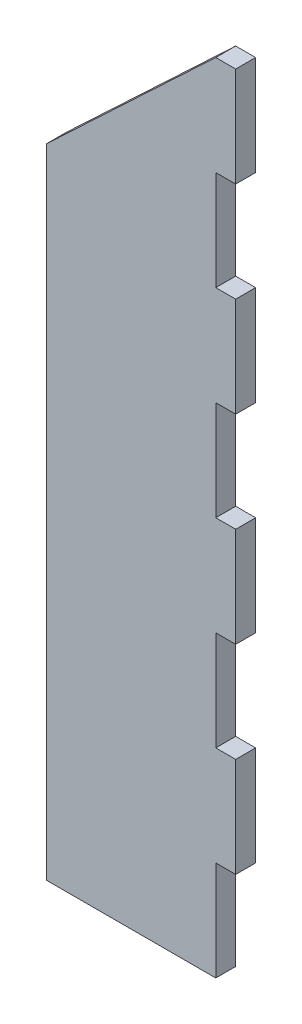
SolidWorks part; units mm, degrees
ref_plane "Front Plane" through (0, 0, 0) normal (0, 0, 1) x (1, 0, 0)
ref_plane "Top Plane" through (0, 0, 0) normal (0, 1, 0) x (1, 0, 0)
ref_plane "Right Plane" through (0, 0, 0) normal (1, 0, 0) x (0, 0, -1)
sketch "Sketch1" plane through (0, 0, 0) normal (0, 0, 1) x (1, 0, 0)
  line L0 (-26.9875, -101.6) -> (-26.9875, 101.6)
  line L1 (-26.9875, 101.6) -> (26.9875, 152.4)
  line L2 (26.9875, 152.4) -> (26.9875, -101.6)
  line L3 (26.9875, -101.6) -> (-26.9875, -101.6)
  line L4 (-26.9875, 0) -> (26.9875, 0) construction
  line L5 (26.9875, 120.65) -> (26.9875, 88.9)
  line L6 (26.9875, 152.4) -> (33.3375, 152.4)
  line L7 (26.9875, 152.4) -> (26.9875, 120.65)
  line L8 (26.9875, 120.65) -> (33.3375, 120.65)
  line L9 (33.3375, 152.4) -> (33.3375, 120.65)
  line L10 (26.9875, 120.65) -> (33.3375, 120.65)
  line L11 (33.3375, 120.65) -> (33.3375, 88.9)
  line L12 (26.9875, 88.9) -> (33.3375, 88.9)
  line L13 (26.9875, 88.9) -> (26.9875, 57.15)
  line L14 (26.9875, 88.9) -> (33.3375, 88.9)
  line L15 (33.3375, 88.9) -> (33.3375, 57.15)
  line L16 (26.9875, 57.15) -> (33.3375, 57.15)
  line L17 (26.9875, 57.15) -> (26.9875, 25.4)
  line L18 (26.9875, 57.15) -> (33.3375, 57.15)
  line L19 (33.3375, 57.15) -> (33.3375, 25.4)
  line L20 (26.9875, 25.4) -> (33.3375, 25.4)
  line L21 (26.9875, 25.4) -> (26.9875, -6.35)
  line L22 (26.9875, 25.4) -> (33.3375, 25.4)
  line L23 (33.3375, 25.4) -> (33.3375, -6.35)
  line L24 (26.9875, -6.35) -> (33.3375, -6.35)
  line L25 (26.9875, -6.35) -> (26.9875, -38.1)
  line L26 (26.9875, -6.35) -> (33.3375, -6.35)
  line L27 (33.3375, -6.35) -> (33.3375, -38.1)
  line L28 (26.9875, -38.1) -> (33.3375, -38.1)
  line L29 (26.9875, -38.1) -> (26.9875, -69.85)
  line L30 (26.9875, -38.1) -> (33.3375, -38.1)
  line L31 (33.3375, -38.1) -> (33.3375, -69.85)
  line L32 (26.9875, -69.85) -> (33.3375, -69.85)
  line L33 (26.9875, -69.85) -> (26.9875, -101.6)
  line L42 (26.9875, -69.85) -> (33.3375, -69.85)
  line L43 (33.3375, -69.85) -> (33.3375, -101.6)
  line L44 (26.9875, -101.6) -> (33.3375, -101.6)
  line L46 (14.2875, -101.6) -> (26.9875, -101.6)
  line L47 (14.2875, -101.6) -> (14.2875, -107.95)
  line L48 (14.2875, -107.95) -> (26.9875, -107.95)
  line L49 (26.9875, -101.6) -> (26.9875, -107.95)
  point P2 (0, 0)
  dimension "D1" = 53.975
  dimension "D2" = 254
  dimension "D3" = 203.2
  dimension "D4" = 6.35
  dimension "D6" = 31.75
  dimension "D7" = 12.7
  dimension "D8" = 6.35
  dimension "D5" = 8
extrude "Boss-Extrude1" add sketch "Sketch1" along normal blind 6.35
sketch "Sketch2" plane through (0, 0, 0) normal (0, 0, -1) x (-1, 0, 0)
  line L1 (-14.2875, -101.6) -> (-26.9875, -101.6)
  line L2 (-14.2875, -101.6) -> (-14.2875, -107.95)
  line L3 (-14.2875, -107.95) -> (-26.9875, -107.95)
  line L4 (-26.9875, -101.6) -> (-26.9875, -107.95)
extrude "Cut-Extrude1" cut sketch "Sketch2" against normal up to surface (6.35 mm away) up to face at (23.0565, 16.3286, 6.35)
equation "\"Height\"= 12in"
equation "\"Depth\"= 7in"
equation "\"WallThickness\"= 0.25in"
equation "\"FloorThickness\"= 0.25in"
equation "\"D1@Sketch1\"=(\"Depth\"-2.75)/2"
equation "\"D4@Sketch1\"=\"WallThickness\""
equation "\"D6@Sketch1\"=\"D2@Sketch1\"/\"D5@Sketch1\""
equation "\"D8@Sketch1\"=\"FloorThickness\""
equation "\"D1@Boss-Extrude1\"=\"WallThickness\""
equation "\"Width\" = 30in"
